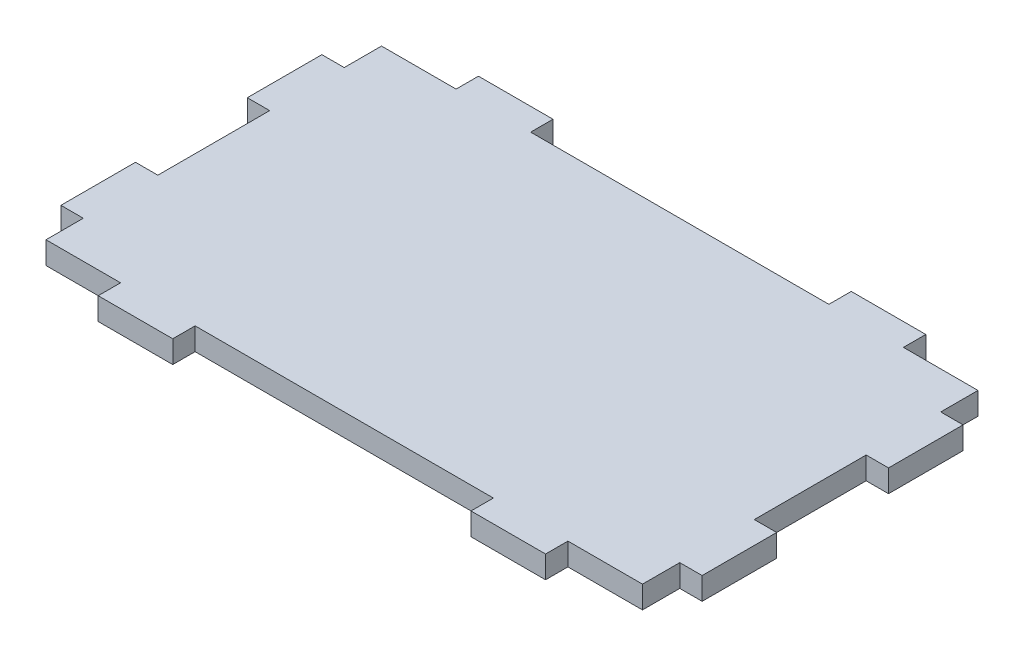
SolidWorks part; units mm, degrees
material "ABS"
ref_plane "Front Plane" through (0, 0, 0) normal (0, 0, 1) x (1, 0, 0)
ref_plane "Top Plane" through (0, 0, 0) normal (0, 1, 0) x (1, 0, 0)
ref_plane "Right Plane" through (0, 0, 0) normal (1, 0, 0) x (0, 0, -1)
sketch "Sketch1" plane through (0, 0, 0) normal (0, 1, 0) x (1, 0, 0)
  line L0 (40, 0) -> (40, 28.2874) construction
  line L1 (0, 0) -> (10, 0)
  line L2 (0, 0) -> (0, 5)
  line L3 (0, 45) -> (10, 45)
  line L4 (80, 0) -> (80, 5)
  line L5 (80, 40) -> (83, 40)
  line L7 (80, 30) -> (83, 30)
  line L8 (83, 40) -> (83, 30)
  line L9 (80, 15) -> (83, 15)
  line L11 (80, 5) -> (83, 5)
  line L12 (83, 15) -> (83, 5)
  line L14 (10, 45) -> (10, 48)
  line L15 (10, 48) -> (20, 48)
  line L16 (20, 45) -> (20, 48)
  line L18 (60, 45) -> (60, 48)
  line L19 (60, 48) -> (70, 48)
  line L20 (70, 45) -> (70, 48)
  line L21 (20, 45) -> (60, 45)
  line L22 (70, 45) -> (80, 45)
  line L23 (80, 40) -> (80, 45)
  line L24 (80, 15) -> (80, 30)
  line L25 (0, 5) -> (-3, 5)
  line L26 (-3, 15) -> (-3, 5)
  line L27 (0, 15) -> (-3, 15)
  line L28 (0, 30) -> (-3, 30)
  line L29 (-3, 40) -> (-3, 30)
  line L30 (0, 40) -> (-3, 40)
  line L31 (0, 40) -> (0, 45)
  line L32 (0, 15) -> (0, 30)
  line L34 (70, 0) -> (70, -3)
  line L35 (60, -3) -> (70, -3)
  line L36 (60, 0) -> (60, -3)
  line L37 (20, 0) -> (20, -3)
  line L38 (10, -3) -> (20, -3)
  line L39 (10, 0) -> (10, -3)
  line L40 (20, 0) -> (60, 0)
  line L41 (70, 0) -> (80, 0)
  dimension "D1" = 45
  dimension "D2" = 80
  dimension "D3" = 10
  dimension "D4" = 10
  dimension "D5" = 3
  dimension "D6" = 3
  dimension "D7" = 5
  dimension "D8" = 15
  dimension "D9" = 10
  dimension "D10" = 10
  dimension "D11" = 3
  dimension "D12" = 3
  dimension "D13" = 10
  dimension "D14" = 40
extrude "Boss-Extrude1" add sketch "Sketch1" along normal blind 3
